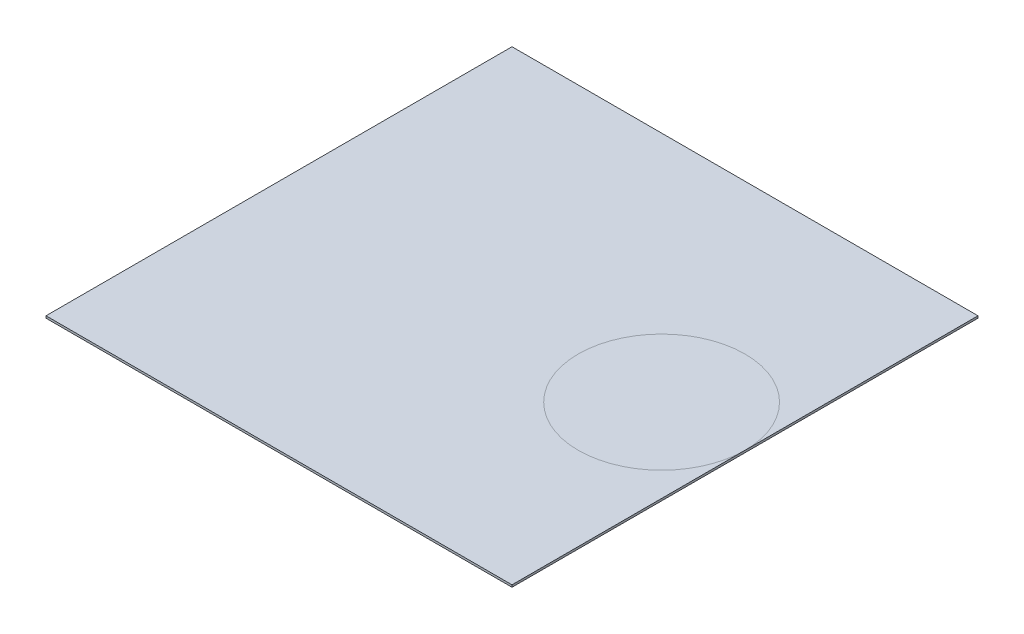
SolidWorks part; units mm, degrees
material "Alumina"
ref_plane "Front Plane" through (0, 0, 0) normal (0, 0, 1) x (1, 0, 0)
ref_plane "Top Plane" through (0, 0, 0) normal (0, 1, 0) x (1, 0, 0)
ref_plane "Right Plane" through (0, 0, 0) normal (1, 0, 0) x (0, 0, -1)
sketch "Sketch1" plane through (0, 0, 0) normal (0, 1, 0) x (1, 0, 0)
  line L1 (-69.85, -69.85) -> (69.85, -69.85)
  line L2 (-69.85, -69.85) -> (-69.85, 69.85)
  line L3 (-69.85, 69.85) -> (69.85, 69.85)
  line L4 (69.85, -69.85) -> (69.85, 69.85)
  line L5 (-69.85, -69.85) -> (69.85, 69.85) construction
  line L6 (-69.85, 69.85) -> (69.85, -69.85) construction
  point P0 (0, 0)
  dimension "D1" = 139.7
extrude "Boss-Extrude1" add sketch "Sketch1" along normal mid plane 0.64
sketch "Sketch2" plane through (0, 0.32, 0) normal (0, 1, 0) x (1, 0, 0)
  line L0 (69.85, -69.85) -> (69.85, 69.85) construction
  circle A1 centre (44.85, 0) radius 25
  point P5 (0, 0)
  dimension "D1" = 50
split line "Split Line1"
